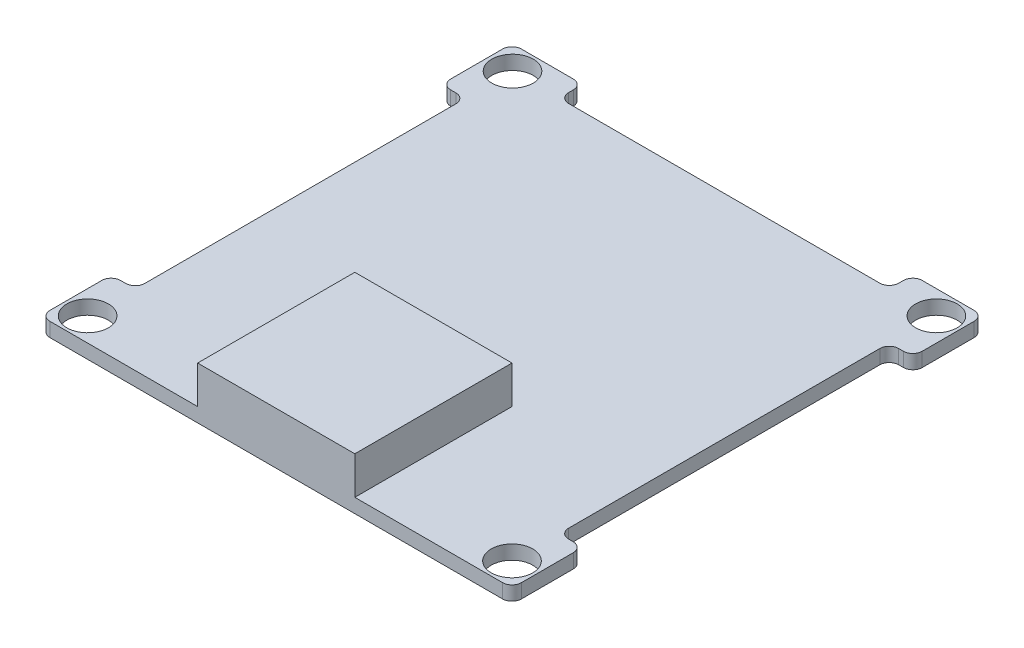
SolidWorks part; units mm, degrees
ref_plane "Front Plane" through (0, 0, 0) normal (0, 0, 1) x (1, 0, 0)
ref_plane "Top Plane" through (0, 0, 0) normal (0, 1, 0) x (1, 0, 0)
ref_plane "Right Plane" through (0, 0, 0) normal (1, 0, 0) x (0, 0, -1)
sketch "Sketch1" plane through (0, 0, 0) normal (0, 1, 0) x (1, 0, 0)
  line L1 (0, 0) -> (50, 0)
  line L2 (0, 0) -> (0, 50)
  line L3 (0, 50) -> (50, 50)
  line L4 (50, 0) -> (50, 50)
  circle A0 centre (2.5555, 47.5) radius 2.2
  circle A1 centre (47.5, 47.5) radius 2.2
  circle A2 centre (2.5, 2.5) radius 2.2
  circle A3 centre (47.5, 2.5) radius 2.2
  point P5 (25, 50)
  point P6 (0, 25)
  point P7 (0, 47.5)
  point P8 (0, 2.5)
  point P9 (2.5, 50)
  point P10 (47.5, 50)
  point P11 (47.5, 0)
  point P12 (2.5555, 47.5)
  point P13 (2.5, 2.5)
  point P14 (25, 0)
  point P15 (47.5, 47.5)
  point P16 (47.5, 2.5)
  dimension "D1" = 50
  dimension "D2" = 50
  dimension "D3" = 22.5
  dimension "D4" = 22.5
  dimension "D5" = 22.5
  dimension "D6" = 22.5
  dimension "D7" = 22.5
extrude "Boss-Extrude1" add sketch "Sketch1" along normal blind 1.5
sketch "Sketch3" plane through (0, 0, 0) normal (0, 1, 0) x (1, 0, 0)
  line L0 (0, 50) -> (0, 0) construction
  line L1 (50, 0) -> (50, 50) construction
  line L2 (0, 42.5) -> (2.5555, 42.5)
  line L3 (0, 42.5) -> (0, 7.5)
  line L4 (0, 7.5) -> (2.5555, 7.5)
  line L5 (2.5555, 42.5) -> (2.5555, 7.5)
  line L6 (50, 42.5) -> (47.5, 42.5)
  line L7 (50, 42.5) -> (50, 7.5)
  line L8 (50, 7.5) -> (47.5, 7.5)
  line L9 (47.5, 42.5) -> (47.5, 7.5)
  line L10 (50, 50) -> (0, 50) construction
  line L12 (7.5, 50) -> (42.5, 50)
  line L13 (7.5, 50) -> (7.5, 47.5)
  line L14 (7.5, 47.5) -> (42.5, 47.5)
  line L15 (42.5, 50) -> (42.5, 47.5)
  point P0 (0, 42.5)
  point P1 (0, 7.5)
  point P16 (7.5, 50)
  point P17 (42.5, 50)
  dimension "D1" = 7.5
  dimension "D2" = 7.5
  dimension "D3" = 7.5
  dimension "D4" = 7.5
extrude "Cut-Extrude1" cut sketch "Sketch3" along normal blind 1.5 contours L3 L2 L5 L4 | L7 L6 L9 L8 | L13 L12 L15 L14
fillet "Fillet8" radius 1 16 edges at (0, 0.75, -7.5) (2.5555, 0.75, -7.5) (0, 0.75, 0) (50, 0.75, 0) (50, 0.75, -7.5) (47.5, 0.75, -7.5) (50, 0.75, -42.5) (47.5, 0.75, -42.5) (50, 0.75, -50) (42.5, 0.75, -50) (42.5, 0.75, -47.5) (7.5, 0.75, -50) (7.5, 0.75, -47.5) (0, 0.75, -50) (0, 0.75, -42.5) (2.5555, 0.75, -42.5)
sketch "Sketch4" plane through (0, 1.5, 0) normal (0, 1, 0) x (1, 0, 0)
  line L0 (1, 0) -> (49, 0) construction
  line L2 (16.6667, 16.6666) -> (33.3333, 16.6666)
  line L3 (16.6667, 16.6666) -> (16.6667, 0)
  line L4 (16.6667, 0) -> (33.3333, 0)
  line L5 (33.3333, 16.6666) -> (33.3333, 0)
  point P0 (25, 0)
  point P1 (33.3333, 0)
  point P4 (16.6667, 0)
  point P5 (33.3333, 16.6666)
  dimension "D1" = 8.3333
  dimension "D2" = 8.3333
  dimension "D3" = 16.6666
extrude "Boss-Extrude2" add sketch "Sketch4" along normal blind 4
